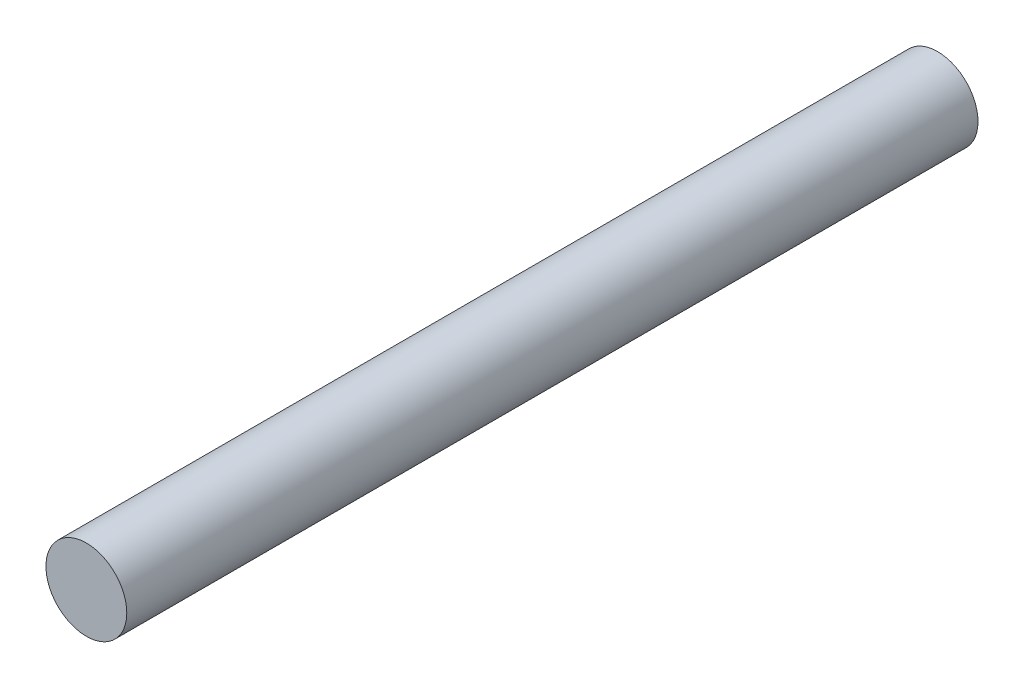
SolidWorks part; units mm, degrees
ref_plane "Front Plane" through (0, 0, 0) normal (0, 0, 1) x (1, 0, 0)
ref_plane "Top Plane" through (0, 0, 0) normal (0, 1, 0) x (1, 0, 0)
ref_plane "Right Plane" through (0, 0, 0) normal (1, 0, 0) x (0, 0, -1)
sketch "Sketch1" plane through (0, 0, 0) normal (0, 0, 1) x (1, 0, 0)
  circle A0 centre (0, 0) radius 4.75
  dimension "D1" = 9.5
extrude "Boss-Extrude1" add sketch "Sketch1" along normal blind 100
